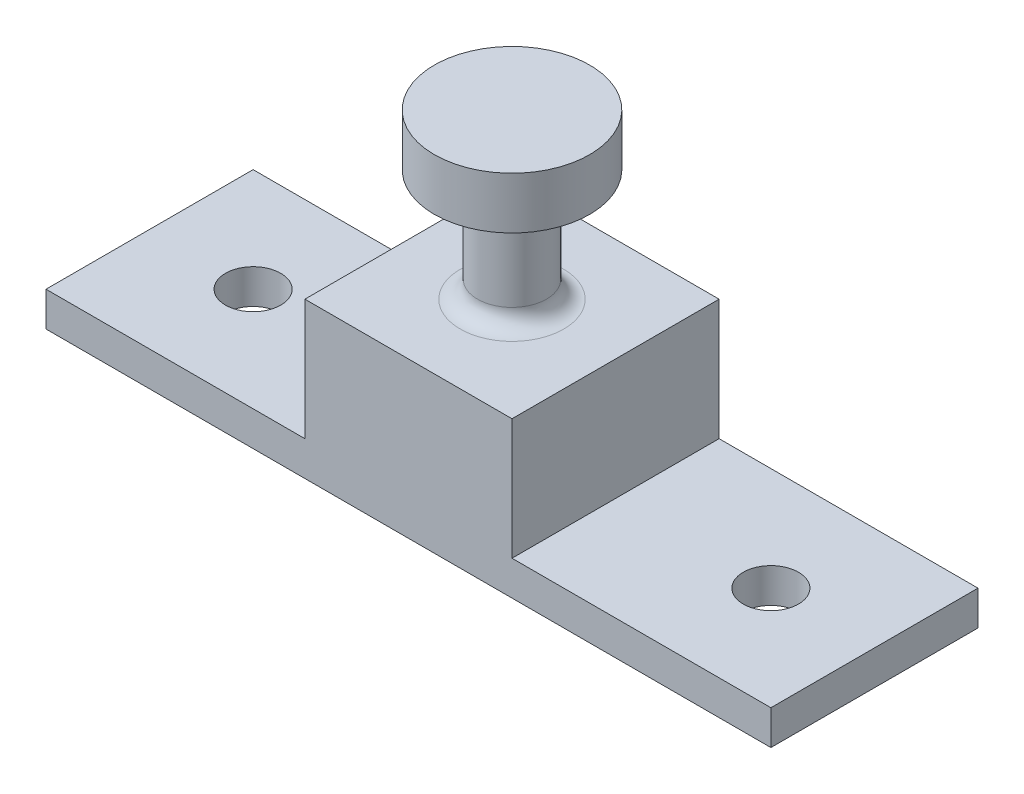
SolidWorks part; units mm, degrees
ref_plane "Alzado" through (0, 0, 0) normal (0, 0, 1) x (1, 0, 0)
ref_plane "Planta" through (0, 0, 0) normal (0, 1, 0) x (1, 0, 0)
ref_plane "Vista lateral" through (0, 0, 0) normal (1, 0, 0) x (0, 0, -1)
sketch "Croquis1" plane through (0, 0, 0) normal (0, 1, 0) x (1, 0, 0)
  line L1 (-21, -6) -> (21, -6)
  line L2 (-21, -6) -> (-21, 6)
  line L3 (-21, 6) -> (21, 6)
  line L4 (21, -6) -> (21, 6)
  line L5 (-21, -6) -> (21, 6) construction
  line L6 (-21, 6) -> (21, -6) construction
  circle A0 centre (-15, 0) radius 1.6
  circle A1 centre (15, 0) radius 1.6
  point P0 (0, 0)
  dimension "D3" = 3.2
  dimension "D4" = 3.2
  dimension "D1" = 12
  dimension "D2" = 42
  dimension "D5" = 15
  dimension "D6" = 15
extrude "Saliente-Extruir1" add sketch "Croquis1" along normal blind 2
sketch "Croquis2" plane through (0, 2, 0) normal (0, 1, 0) x (1, 0, 0)
  line L0 (21, 6) -> (-21, 6) construction
  line L1 (-6, -6) -> (6, -6)
  line L2 (-6, -6) -> (-6, 6)
  line L3 (-6, 6) -> (6, 6)
  line L4 (6, -6) -> (6, 6)
  line L5 (-6, -6) -> (6, 6) construction
  line L6 (-6, 6) -> (6, -6) construction
  point P0 (0, 0)
  dimension "D1" = 12
extrude "Saliente-Extruir2" add sketch "Croquis2" along normal blind 7
sketch "Croquis3" plane through (0, 9, 0) normal (0, 1, 0) x (1, 0, 0)
  circle A0 centre (0, 0) radius 2
  dimension "D1" = 4
extrude "Saliente-Extruir3" add sketch "Croquis3" along normal blind 6.5
sketch "Croquis4" plane through (0, 15.5, 0) normal (0, 1, 0) x (1, 0, 0)
  circle A0 centre (0, 0) radius 4.5
  dimension "D1" = 9
extrude "Saliente-Extruir4" add sketch "Croquis4" along normal blind 3
fillet "Redondeo1" radius 1 1 edges at (0, 9, 2)
